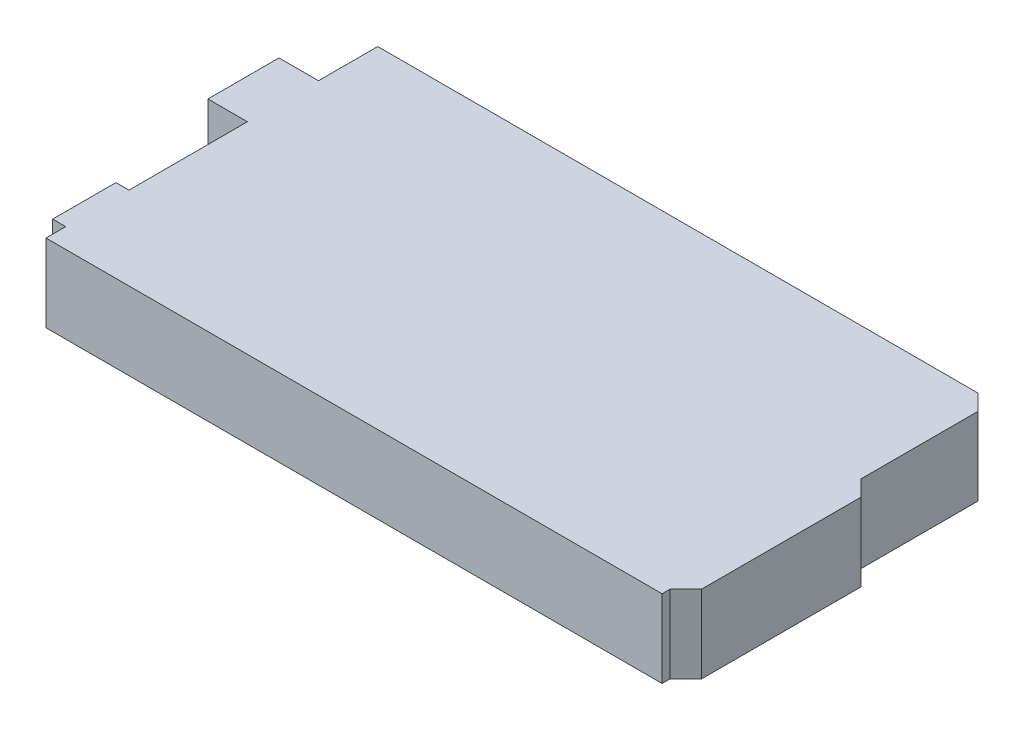
SolidWorks part; units mm, degrees
ref_plane "Front Plane" through (0, 0, 0) normal (0, 0, 1) x (1, 0, 0)
ref_plane "Top Plane" through (0, 0, 0) normal (0, 1, 0) x (1, 0, 0)
ref_plane "Right Plane" through (0, 0, 0) normal (1, 0, 0) x (0, 0, -1)
sketch "Sketch1" plane through (0, 0, 0) normal (0, 1, 0) x (1, 0, 0)
  line L0 (-118.859, -25.5954) -> (-118.859, -22.4204)
  line L1 (-118.859, 27.7446) -> (-22.339, 27.7446)
  line L2 (-22.339, 27.7446) -> (-19.799, 25.2046)
  line L3 (-19.799, 25.2046) -> (-19.799, 6.3826)
  line L4 (-19.799, 6.3826) -> (-17.259, 3.8426)
  line L5 (-17.259, 3.8426) -> (-17.259, -21.7854)
  line L6 (-17.259, -21.7854) -> (-19.799, -24.3254)
  line L7 (-19.799, -24.3254) -> (-19.799, -25.5954)
  line L8 (-19.799, -25.5954) -> (-118.859, -25.5954)
  line L9 (-118.859, 18.2196) -> (-125.209, 18.2196)
  line L10 (-125.209, 18.2196) -> (-125.209, 6.7896)
  line L11 (-125.209, 6.7896) -> (-118.859, 6.7896)
  line L12 (-118.859, -12.2604) -> (-120.959, -12.2604)
  line L13 (-120.959, -12.2604) -> (-120.959, -22.4204)
  line L14 (-120.959, -22.4204) -> (-118.859, -22.4204)
  line L15 (-118.859, -12.2604) -> (-118.859, 6.7896)
  line L16 (-118.859, 18.2196) -> (-118.859, 27.7446)
  dimension "D1" = 53.34
  dimension "D2" = 101.6
  dimension "D3" = 2.54
  dimension "D4" = 2.54
  dimension "D5" = 2.54
  dimension "D6" = 1.27
  dimension "D7" = 90
  dimension "D8" = 2.54
  dimension "D9" = 2.1
  dimension "D10" = 3.175
  dimension "D11" = 10.16
  dimension "D12" = 6.35
  dimension "D13" = 32.385
  dimension "D14" = 43.815
extrude "Boss-Extrude1" add sketch "Sketch1" along normal blind 12.5
